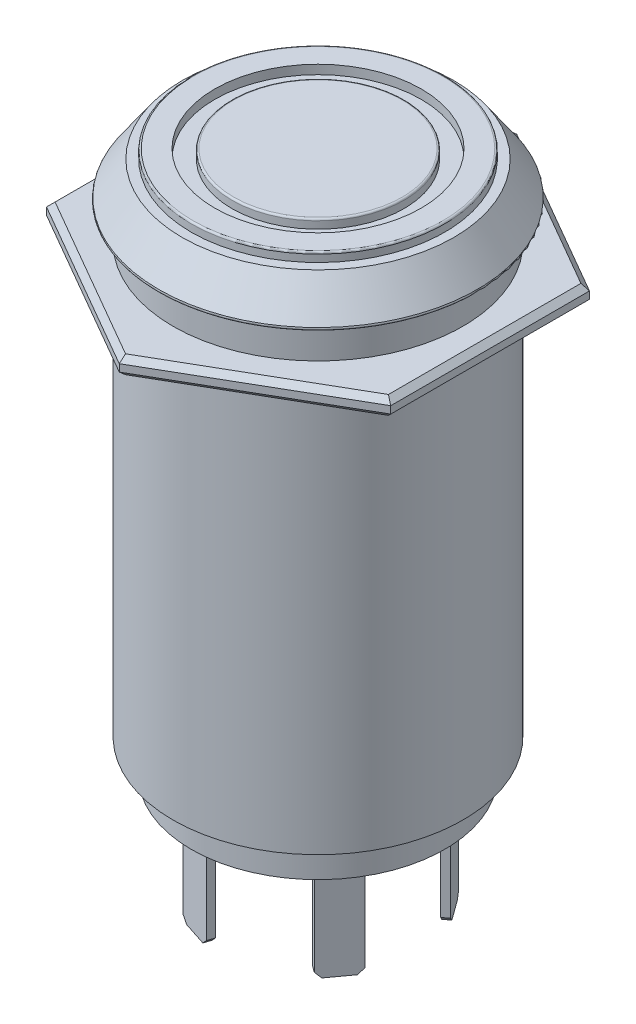
SolidWorks part; units mm, degrees
ref_plane "Front Plane" through (0, 0, 0) normal (0, 0, 1) x (1, 0, 0)
ref_plane "Top Plane" through (0, 0, 0) normal (0, 1, 0) x (1, 0, 0)
ref_plane "Right Plane" through (0, 0, 0) normal (1, 0, 0) x (0, 0, -1)
sketch "Sketch1" plane through (0, 0, 0) normal (0, 0, 1) x (1, 0, 0)
  line L0 (0, 14.75) -> (0, -14.75) construction
  line L1 (0, 14.75) -> (-7.5, 14.75)
  line L2 (-7.5, 14.75) -> (-8.9, 12.75)
  line L3 (-8.9, 12.75) -> (-8, 12.75)
  line L4 (-8, 12.75) -> (-8, -12.85)
  line L5 (-8, -12.85) -> (-7, -12.85)
  line L6 (-7, -12.85) -> (-7, -14.75)
  line L7 (-7, -14.75) -> (0, -14.75)
  line L8 (0, 14.75) -> (0, -14.75)
  dimension "D1" = 2
  dimension "D2" = 27.6
  dimension "D3" = 16
  dimension "D4" = 14
  dimension "D5" = 1.9
  dimension "D6" = 17.8
  dimension "D7" = 15
revolve "Revolve1" add sketch "Sketch1" angle 360 about L0
sketch "Sketch2" plane through (0, -14.75, 0) normal (0, -1, 0) x (1, 0, 0)
  line L0 (-10.3604, 0) -> (10.3338, 0) construction
  line L1 (-5.4, 1) -> (-5, 1)
  line L2 (-5.4, 1) -> (-5.4, -1)
  line L3 (-5.4, -1) -> (-5, -1)
  line L4 (-5, 1) -> (-5, -1)
  line L5 (-0.7176, 5.4447) -> (-0.594, 5.0643)
  line L6 (-0.7176, 5.4447) -> (-2.6197, 4.8267)
  line L7 (-2.6197, 4.8267) -> (-2.4961, 4.4463)
  line L8 (-0.594, 5.0643) -> (-2.4961, 4.4463)
  line L9 (4.9565, 2.365) -> (4.6329, 2.1299)
  line L10 (4.9565, 2.365) -> (3.7809, 3.9831)
  line L11 (3.7809, 3.9831) -> (3.4573, 3.7479)
  line L12 (4.6329, 2.1299) -> (3.4573, 3.7479)
  line L13 (3.7809, -3.9831) -> (3.4573, -3.7479)
  line L14 (3.7809, -3.9831) -> (4.9565, -2.365)
  line L15 (4.9565, -2.365) -> (4.6329, -2.1299)
  line L16 (3.4573, -3.7479) -> (4.6329, -2.1299)
  line L17 (-2.6197, -4.8267) -> (-2.4961, -4.4463)
  line L18 (-2.6197, -4.8267) -> (-0.7176, -5.4447)
  line L19 (-0.7176, -5.4447) -> (-0.594, -5.0643)
  line L20 (-2.4961, -4.4463) -> (-0.594, -5.0643)
  point P7 (-5, 0)
  point P27 (0, 0)
  dimension "D1" = 2
  dimension "D2" = 0.4
  dimension "D3" = 5
  dimension "D4" = 5
extrude "Boss-Extrude1" add sketch "Sketch2" along normal blind 5.8
chamfer "Chamfer1" distance 0.3 angle 45 10 edges at (-0.6558, -20.55, 5.2545) (-2.5579, -20.55, 4.6365) (3.6191, -20.55, 3.8655) (4.7947, -20.55, 2.2475) (4.7947, -20.55, -2.2475) (3.6191, -20.55, -3.8655) (-0.6558, -20.55, -5.2545) (-2.5579, -20.55, -4.6365) (-5.2, -20.55, -1) (-5.2, -20.55, 1)
sketch "Sketch3" plane through (0, 14.75, 0) normal (0, 1, 0) x (1, 0, 0)
  circle A0 centre (0, 0) radius 7
  dimension "D1" = 14
extrude "Boss-Extrude2" add sketch "Sketch3" along normal blind 0.5
sketch "Sketch4" plane through (0, 15.25, 0) normal (0, 1, 0) x (1, 0, 0)
  circle A0 centre (0, 0) radius 5.7
  circle A1 centre (0, 0) radius 4.75
  dimension "D1" = 11.4
  dimension "D2" = 9.5
extrude "Cut-Extrude1" cut sketch "Sketch4" against normal blind 0.5
fillet "Fillet1" radius 0.1 2 edges at (0, 15.25, 7) (0, 15.25, 4.75)
fillet "Fillet2" radius 0.1 1 edges at (0, 12.75, 8.9)
ref_plane "Plane1" through (0, 10.75, 0) normal (0, -1, 0) x (-1, 0, 0)
sketch "Sketch5" plane through (0, 10.75, 0) normal (0, -1, 0) x (-1, 0, 0)
  line L0 (0, 10.9697) -> (0, -10.9697) construction
  line L1 (0, 10.9697) -> (-9.5, 5.4848)
  line L2 (-9.5, 5.4848) -> (-9.5, -5.4848)
  line L3 (-9.5, -5.4848) -> (0, -10.9697)
  line L4 (0, -10.9697) -> (9.5, -5.4848)
  line L5 (9.5, -5.4848) -> (9.5, 5.4848)
  line L6 (9.5, 5.4848) -> (0, 10.9697)
  circle A0 centre (0, 0) radius 9.5 construction
  circle A1 centre (0, 0) radius 8 construction
  circle A2 centre (0, 0) radius 8
  dimension "D1" = 19
extrude "Boss-Extrude3" add sketch "Sketch5" along normal blind 1
chamfer "Chamfer2" distance 0.3 angle 45 12 edges at (4.75, 9.75, -8.2272) (9.5, 9.75, 0) (4.75, 9.75, 8.2272) (-4.75, 9.75, 8.2272) (-4.75, 9.75, -8.2272) (-9.5, 9.75, 0) (4.75, 10.75, 8.2272) (-4.75, 10.75, 8.2272) (-9.5, 10.75, 0) (-4.75, 10.75, -8.2272) (4.75, 10.75, -8.2272) (9.5, 10.75, 0)
